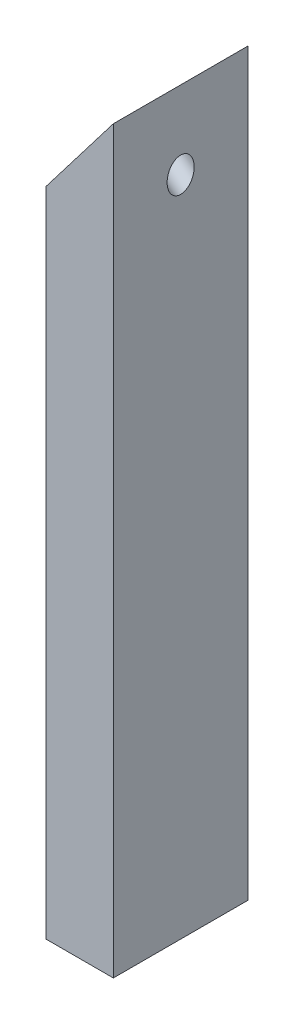
SolidWorks part; units mm, degrees
material "Brass"
ref_plane "Front Plane" through (0, 0, 0) normal (0, 0, 1) x (1, 0, 0)
ref_plane "Top Plane" through (0, 0, 0) normal (0, 1, 0) x (1, 0, 0)
ref_plane "Right Plane" through (0, 0, 0) normal (1, 0, 0) x (0, 0, -1)
sketch "Sketch1" plane through (0, 0, 0) normal (0, 0, 1) x (1, 0, 0)
  line L0 (-81.049, -45.6084) -> (-39785.8735, 30343.9772) construction
  line L1 (-1075.7055, -71.0084) -> (48924.2945, -71.0084) construction
  line L2 (0, 38.1) -> (0, 38.1001) construction
  line L3 (-692.523, -844.5158) -> (29697.0626, 38860.3087) construction
  line L4 (-81.049, -45.6084) -> (-81.049, -71.0084) construction
  line L5 (0, 60.2844) -> (-39704.8245, 30449.8699) construction
  line L6 (0, 60.2844) -> (0, -71.0084) construction
  line L7 (-6.35, 51.9879) -> (-6.35, -71.0084) construction
  line L8 (6.35, 68.5808) -> (6.35, -71.0084) construction
  line L9 (-6.35, 51.9879) -> (6.35, 68.5808)
  line L10 (6.35, 68.5808) -> (6.35, -71.0084)
  line L11 (6.35, -71.0084) -> (-6.35, -71.0084)
  line L12 (-6.35, -71.0084) -> (-6.35, 51.9879)
  dimension "D1" = 133.35
  dimension "D2" = 25.4
  dimension "D3" = 37.43
  dimension "D4" = 12.7
  dimension "D5" = 6.35
  dimension "hyp" = 20.8953
extrude "Extrude1" add sketch "Sketch1" along normal blind 25.4
hole_wizard "1/4-20 Tapped Hole1" positions "Sketch2" profile "Sketch3" tap size "1/4-20" standard "Ansi Inch"
sketch "Sketch2" plane through (-36.8664, 12.1174, 18.0613) normal (-0.7941, 0.6078, 0) x (0.6078, 0.7941, 0)
  point P0 (59.4462, 5.3613)
sketch "Sketch3" plane through (-0.7356, 59.3233, 12.7) normal (0, 0, 1) x (-0.6078, -0.7941, 0)
  line L0 (0, 0) -> (0, 17.5358)
  line L1 (0, 17.5358) -> (2.5527, 16.002)
  line L2 (2.5527, 16.002) -> (2.5527, 0)
  line L5 (2.5527, 0) -> (0, 0)
  line L10 (0, 17.5358) -> (-2.5527, 16.002) construction
  line L11 (0, -6.35) -> (0, 107.95) construction
  dimension "Tap Drill Dia." = 5.1054
  dimension "Tap Drill Depth" = 16.002
  dimension "Drill Angle" = 118
cosmetic thread "Hole Thread2"
hole_wizard "1/4-20 Tapped Hole2" positions "Sketch4" profile "Sketch5" tap size "1/4-20" standard "Ansi Inch"
sketch "Sketch4" plane through (-43.2423, -71.0084, 18.0613) normal (0, -1, 0) x (-1, 0, 0)
  point P0 (-43.1109, 5.3613)
sketch "Sketch5" plane through (-0.1314, -71.0084, 12.7) normal (1, 0, 0) x (0, 0, -1)
  line L0 (0, 0) -> (0, 17.5358)
  line L1 (0, 17.5358) -> (2.5527, 16.002)
  line L2 (2.5527, 16.002) -> (2.5527, 0)
  line L3 (2.5527, 0) -> (0, 0)
  line L4 (0, 17.5358) -> (-2.5527, 16.002) construction
  line L5 (0, -6.35) -> (0, 107.95) construction
  dimension "Tap Drill Dia." = 5.1054
  dimension "Tap Drill Depth" = 16.002
  dimension "Drill Angle" = 118
cosmetic thread "Hole Thread3"
